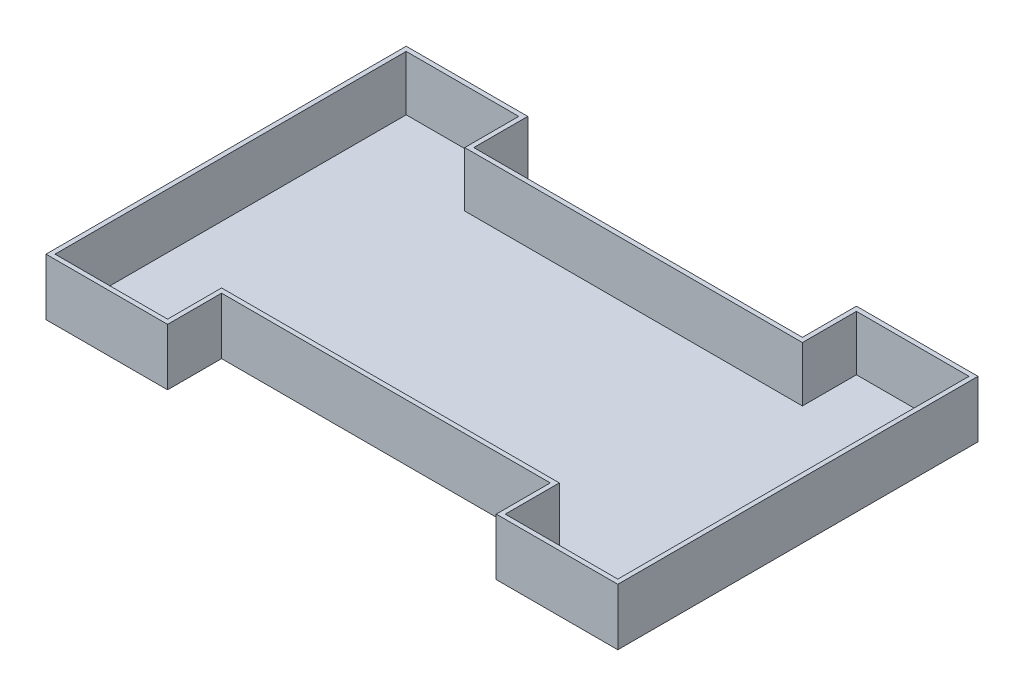
SolidWorks part; units mm, degrees
ref_plane "Front Plane" through (0, 0, 0) normal (0, 0, 1) x (1, 0, 0)
ref_plane "Top Plane" through (0, 0, 0) normal (0, 1, 0) x (1, 0, 0)
ref_plane "Right Plane" through (0, 0, 0) normal (1, 0, 0) x (0, 0, -1)
sketch "Sketch1" plane through (0, 0, 0) normal (0, 1, 0) x (1, 0, 0)
  line L1 (403.225, -254) -> (-403.225, -254)
  line L2 (403.225, -254) -> (403.225, 254)
  line L3 (403.225, 254) -> (-403.225, 254)
  line L4 (-403.225, -254) -> (-403.225, 254)
  line L5 (403.225, -254) -> (-403.225, 254) construction
  line L6 (403.225, 254) -> (-403.225, -254) construction
  point P0 (0, 0)
  point P6 (-400, -244.4495)
  dimension "D1" = 806.45
  dimension "D2" = 508
extrude "Boss-Extrude1" add sketch "Sketch1" along normal blind 2.54
sketch "Sketch2" plane through (0, 2.54, 0) normal (0, 1, 0) x (1, 0, 0)
  line L0 (-403.225, -254) -> (403.225, -254) construction
  line L1 (-231.775, -254) -> (231.775, -254)
  line L2 (-231.775, -254) -> (-231.775, -177.8)
  line L3 (-231.775, -177.8) -> (231.775, -177.8)
  line L4 (231.775, -254) -> (231.775, -177.8)
  line L5 (403.225, 254) -> (-403.225, 254) construction
  line L6 (231.775, 254) -> (-231.775, 254)
  line L7 (231.775, 254) -> (231.775, 177.8)
  line L8 (231.775, 177.8) -> (-231.775, 177.8)
  line L9 (-231.775, 254) -> (-231.775, 177.8)
  line L10 (-403.225, 254) -> (-403.225, -254) construction
  line L11 (403.225, -254) -> (403.225, 254) construction
  dimension "D1" = 171.45
  dimension "D2" = 171.45
  dimension "D3" = 355.6
extrude "Cut-Extrude1" cut sketch "Sketch2" against normal blind 2.54
sketch "Sketch3" plane through (0, 2.54, 0) normal (0, 1, 0) x (1, 0, 0)
  line L1 (238.125, 171.45) -> (-238.125, 171.45)
  line L2 (-238.125, 171.45) -> (-238.125, 247.65)
  line L3 (-238.125, 247.65) -> (-396.875, 247.65)
  line L4 (-396.875, 247.65) -> (-396.875, -247.65)
  line L5 (-396.875, -247.65) -> (-238.125, -247.65)
  line L6 (-238.125, -247.65) -> (-238.125, -171.45)
  line L7 (-238.125, -171.45) -> (238.125, -171.45)
  line L8 (238.125, -171.45) -> (238.125, -247.65)
  line L9 (238.125, -247.65) -> (396.875, -247.65)
  line L10 (396.875, -247.65) -> (396.875, 247.65)
  line L11 (396.875, 247.65) -> (238.125, 247.65)
  line L12 (238.125, 247.65) -> (238.125, 171.45)
  line L13 (-231.775, -254) -> (-231.775, -177.8)
  line L14 (-231.775, -177.8) -> (231.775, -177.8)
  line L15 (231.775, -177.8) -> (231.775, -254)
  line L16 (231.775, -254) -> (403.225, -254)
  line L17 (403.225, -254) -> (403.225, 254)
  line L18 (403.225, 254) -> (231.775, 254)
  line L19 (231.775, 254) -> (231.775, 177.8)
  line L20 (231.775, 177.8) -> (-231.775, 177.8)
  line L21 (-231.775, 177.8) -> (-231.775, 254)
  line L22 (-231.775, 254) -> (-403.225, 254)
  line L23 (-403.225, 254) -> (-403.225, -254)
  line L24 (-403.225, -254) -> (-231.775, -254)
  line L25 (-231.775, -254) -> (-231.775, -177.8)
  line L26 (-231.775, -177.8) -> (231.775, -177.8)
  line L27 (231.775, -177.8) -> (231.775, -254)
  line L28 (231.775, -254) -> (403.225, -254)
  line L29 (403.225, -254) -> (403.225, 254)
  line L30 (403.225, 254) -> (231.775, 254)
  line L31 (231.775, 254) -> (231.775, 177.8)
  line L32 (231.775, 177.8) -> (-231.775, 177.8)
  line L33 (-231.775, 177.8) -> (-231.775, 254)
  line L34 (-231.775, 254) -> (-403.225, 254)
  line L35 (-403.225, 254) -> (-403.225, -254)
  line L36 (-403.225, -254) -> (-231.775, -254)
  dimension "D1" = 0
  dimension "D2" = 6.35
extrude "Boss-Extrude2" add sketch "Sketch3" along normal blind 77.47
